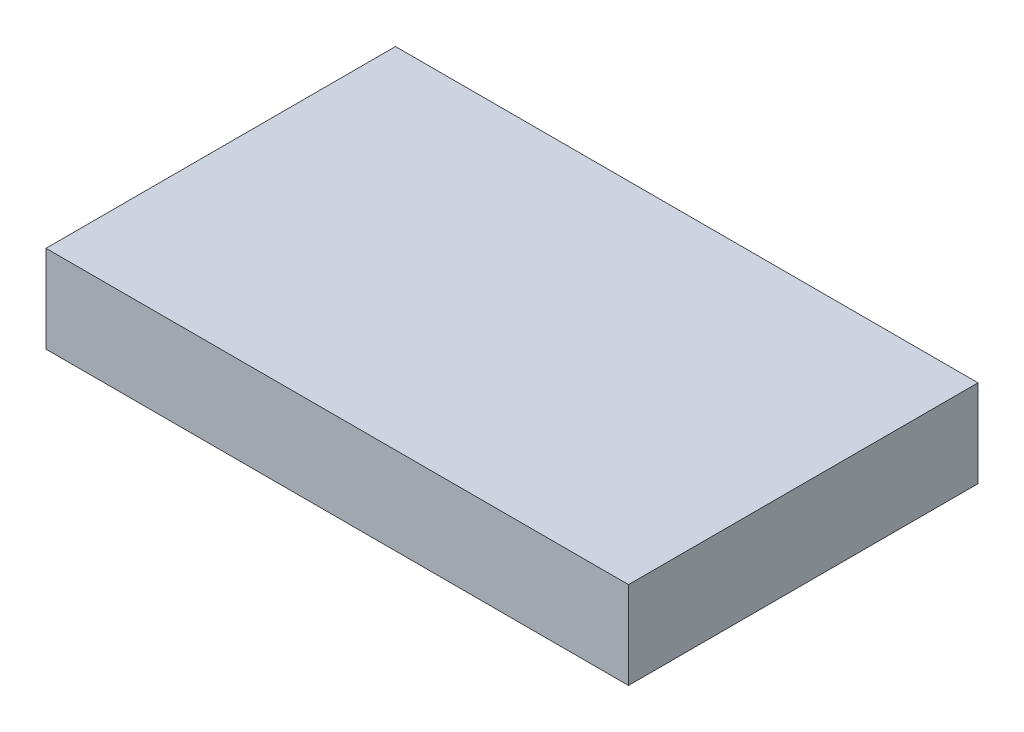
SolidWorks part; units mm, degrees
ref_plane "前视基准面" through (0, 0, 0) normal (0, 0, 1) x (1, 0, 0)
ref_plane "上视基准面" through (0, 0, 0) normal (0, 1, 0) x (1, 0, 0)
ref_plane "右视基准面" through (0, 0, 0) normal (1, 0, 0) x (0, 0, -1)
sketch "草图1" plane through (0, 0, 0) normal (0, 0, 1) x (1, 0, 0)
  line L0 (-40, 0) -> (40, 0)
  line L1 (40, 0) -> (40, 12)
  line L2 (40, 12) -> (-40, 12)
  line L3 (-40, 12) -> (-40, 0)
  dimension "D1" = 80
  dimension "D2" = 12
extrude "凸台-拉伸1" add sketch "草图1" along normal blind 48
